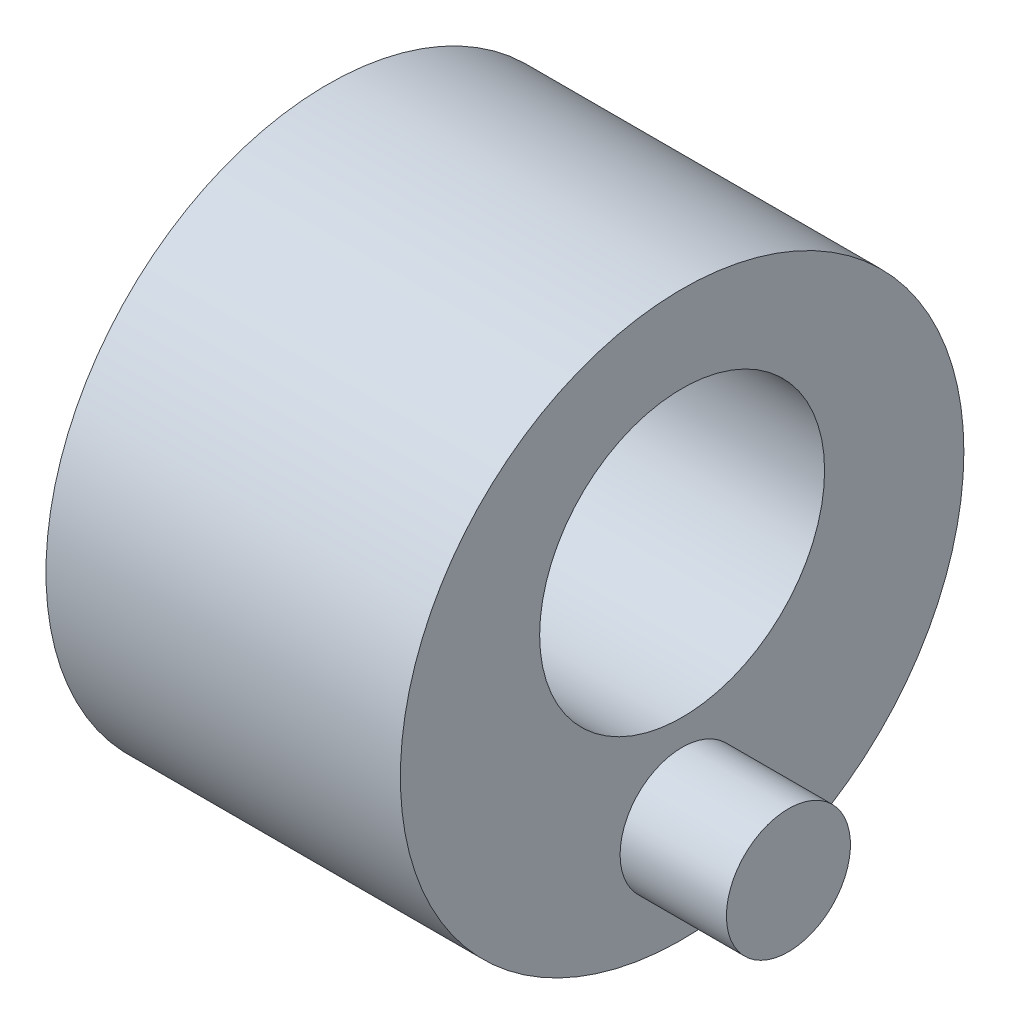
SolidWorks part; units mm, degrees
ref_plane "Front Plane" through (0, 0, 0) normal (0, 0, 1) x (1, 0, 0)
ref_plane "Top Plane" through (0, 0, 0) normal (0, 1, 0) x (1, 0, 0)
ref_plane "Right Plane" through (0, 0, 0) normal (1, 0, 0) x (0, 0, -1)
sketch "Sketch1" plane through (0, 0, 0) normal (1, 0, 0) x (0, 0, -1)
  circle A0 centre (0, 0) radius 100.965
  dimension "D1" = 201.93
extrude "Boss-Extrude1" add sketch "Sketch1" against normal blind 127
sketch "Sketch2" plane through (0, 0, 0) normal (1, 0, 0) x (0, 0, -1)
  line L0 (0, -998.1793) -> (0, 49001.8207) construction
  line L1 (-977.9245, 19.05) -> (49022.0755, 19.05) construction
  circle A0 centre (0, 19.05) radius 51.054
  dimension "D2" = 102.108
  dimension "D1" = 19.05
extrude "Cut-Extrude1" cut sketch "Sketch2" against normal through all
sketch "Sketch3" plane through (0, 0, 0) normal (1, 0, 0) x (0, 0, -1)
  line L0 (0, -1000) -> (0, 49000) construction
  line L1 (-1011.6067, -63.5) -> (48988.3933, -63.5) construction
  circle A0 centre (0, -63.5) radius 22.225
  dimension "D2" = 44.45
  dimension "D1" = 63.5
extrude "Boss-Extrude2" add sketch "Sketch3" along normal blind 38.1
